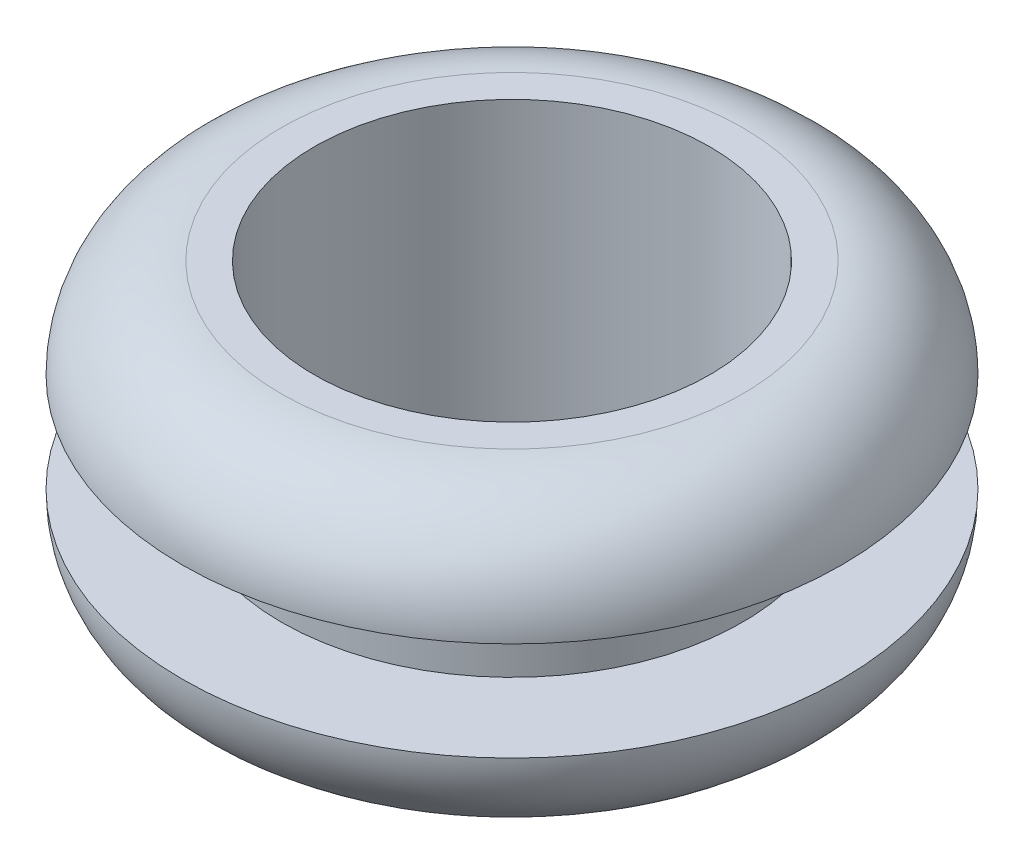
SolidWorks part; units mm, degrees
ref_plane "Front" through (0, 0, 0) normal (0, 0, 1) x (1, 0, 0)
ref_plane "Top" through (0, 0, 0) normal (0, 1, 0) x (1, 0, 0)
ref_plane "Right" through (0, 0, 0) normal (1, 0, 0) x (0, 0, -1)
sketch "Sketch1" plane through (0, 0, 0) normal (1, 0, 0) x (0, 0, -1)
  line L0 (0, -3.5719) -> (0, 3.5719) construction
  line L1 (0, 1.1906) -> (0, -1.1906) construction
  line L2 (-7.9375, 3.5719) -> (7.9375, 3.5719) construction
  line L3 (-4.7625, 1.1906) -> (4.7625, 1.1906) construction
  line L4 (-5.5562, 0) -> (5.5562, 0) construction
  point P12 (-4.7625, 1.1906)
  point P13 (4.7625, 1.1906)
  point P14 (-5.5562, 0)
  point P15 (5.5562, 0)
  point P16 (-7.9375, 3.5719)
  point P17 (0, -3.5719)
  point P18 (7.9375, 3.5719)
  point P19 (0, 3.5719)
  point P20 (0, 1.1906)
  point P21 (0, -1.1906)
  dimension "Overall Height E" = 7.1437
  dimension "Material Thickness B" = 2.3813
  dimension "Flange Diameter D" = 15.875
  dimension "ID C" = 9.525
  dimension "For ID A" = 11.1125
sketch "Sketch2" plane through (0, 0, 0) normal (1, 0, 0) x (0, 0, -1)
  line L0 (-4.7625, -3.5719) -> (-4.7625, 3.5719)
  line L1 (-4.7625, 3.5719) -> (-5.5563, 3.5719)
  line L2 (-5.5563, 1.1906) -> (-5.5563, -1.1906)
  line L3 (-5.5563, 1.1906) -> (-7.9375, 1.1906)
  line L4 (-5.5563, -1.1906) -> (-7.9375, -1.1906)
  line L5 (-4.7625, -3.5719) -> (-5.5563, -3.5719)
  arc A0 (-7.9375, 1.1906) -> (-5.5563, 3.5719) centre (-5.5562, 1.1906) cw
  arc A1 (-7.9375, -1.1906) -> (-5.5563, -3.5719) centre (-5.5562, -1.1906) ccw
  point P4 (-7.9375, 1.1906)
revolve "Revolve1" add sketch "Sketch2" angle 360 about L0
ref_plane "Plane1" through (0, 3.5719, 0) normal (0, -1, 0) x (0, 0, -1)
sketch "Sketch3" plane through (0, 3.5719, 0) normal (0, -1, 0) x (0, 0, -1)
  line L0 (0, -7.9375) -> (0, 7.9375) construction
  line L1 (-7.9375, 0) -> (7.9375, 0) construction
  line L2 (0, 4.7625) -> (0, -4.7625) construction
  line L3 (-4.7625, 0) -> (4.7625, 0) construction
  line L4 (0, 5.5562) -> (0, -5.5562) construction
  line L5 (-5.5562, 0) -> (5.5562, 0) construction
  point P11 (0, 7.9375)
  point P12 (0, 4.7625)
  point P13 (0, -4.7625)
  point P14 (0, -7.9375)
  point P19 (0, -5.5562)
  point P20 (0, 5.5562)
